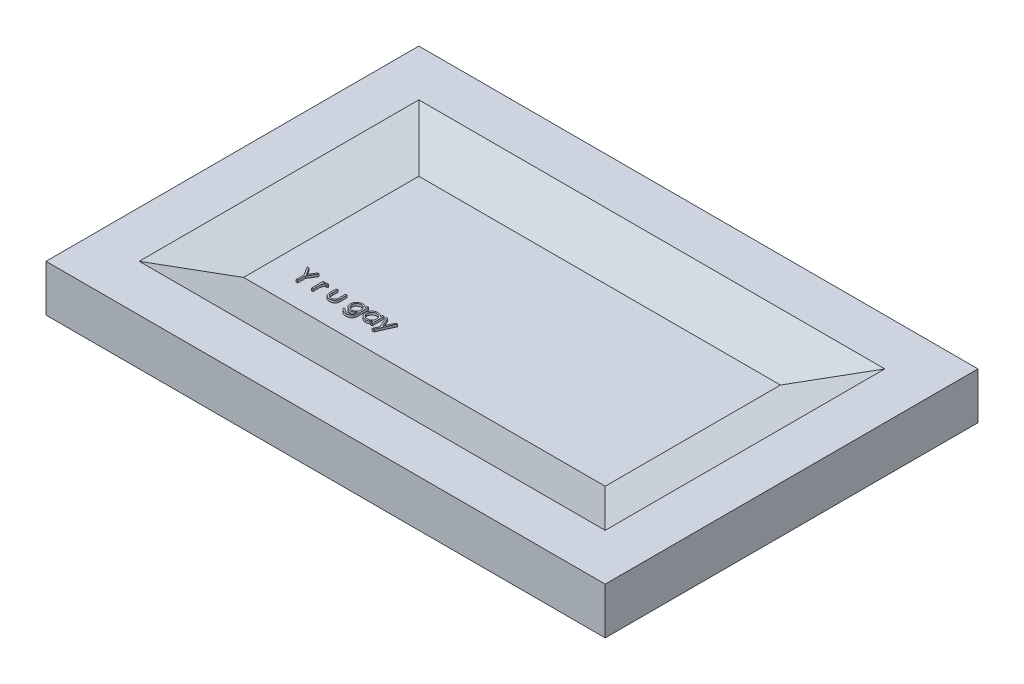
SolidWorks part; units mm, degrees
ref_plane "Front Plane" through (0, 0, 0) normal (0, 0, 1) x (1, 0, 0)
ref_plane "Top Plane" through (0, 0, 0) normal (0, 1, 0) x (1, 0, 0)
ref_plane "Right Plane" through (0, 0, 0) normal (1, 0, 0) x (0, 0, -1)
sketch "Sketch1" plane through (0, 0, 0) normal (0, 1, 0) x (1, 0, 0)
  line L1 (60, -40) -> (-60, -40)
  line L2 (60, -40) -> (60, 40)
  line L3 (60, 40) -> (-60, 40)
  line L4 (-60, -40) -> (-60, 40)
  line L5 (60, -40) -> (-60, 40) construction
  line L6 (60, 40) -> (-60, -40) construction
  point P0 (0, 0)
  dimension "D1" = 80
  dimension "D2" = 120
extrude "Boss-Extrude1" add sketch "Sketch1" along normal mid plane 10
sketch3d "3DSketch1"
  line L0 (-50, 5, 30) -> (50, 5, 30)
  line L1 (50, 5, 30) -> (50, 5, -30)
  line L2 (50, 5, -30) -> (-50, 5, -30)
  line L3 (-50, 5, -30) -> (-50, 5, 30)
  line L4 (-50, 5, 30) -> (50, 5, 30)
  line L5 (50, 5, 30) -> (50, 5, -30)
  line L6 (50, 5, -30) -> (-50, 5, -30)
  line L7 (-50, 5, -30) -> (-50, 5, 30)
  dimension "D1" = 10
extrude "Cut-Extrude1" cut sketch "3DSketch1" along direction (0, 1, 0) on the side of the normal blind 3 draft 75 contours L4 L5 L6 L7
sketch "Sketch2" plane through (0, -5, 0) normal (0, -1, 0) x (1, 0, 0)
  line L8 (-50, 30) -> (-50, -30)
  line L9 (-50, -30) -> (50, -30)
  line L10 (50, -30) -> (50, 30)
  line L11 (50, 30) -> (-50, 30)
  line L12 (-50, 30) -> (-50, -30)
  line L13 (-50, -30) -> (50, -30)
  line L14 (50, -30) -> (50, 30)
  line L15 (50, 30) -> (-50, 30)
  dimension "D1" = 10
extrude "Cut-Extrude2" cut sketch "Sketch2" against normal blind 3 draft 75
sketch "Sketch3" plane through (0, 2, 0) normal (0, 1, 0) x (1, 0, 0)
  line L0 (-33.58, -14.0224) -> (-8.6103, -14.0224) construction
  text T0 "Y r u gay\r\n"
extrude "Boss-Extrude2" add sketch "Sketch3" along normal blind 0.5
